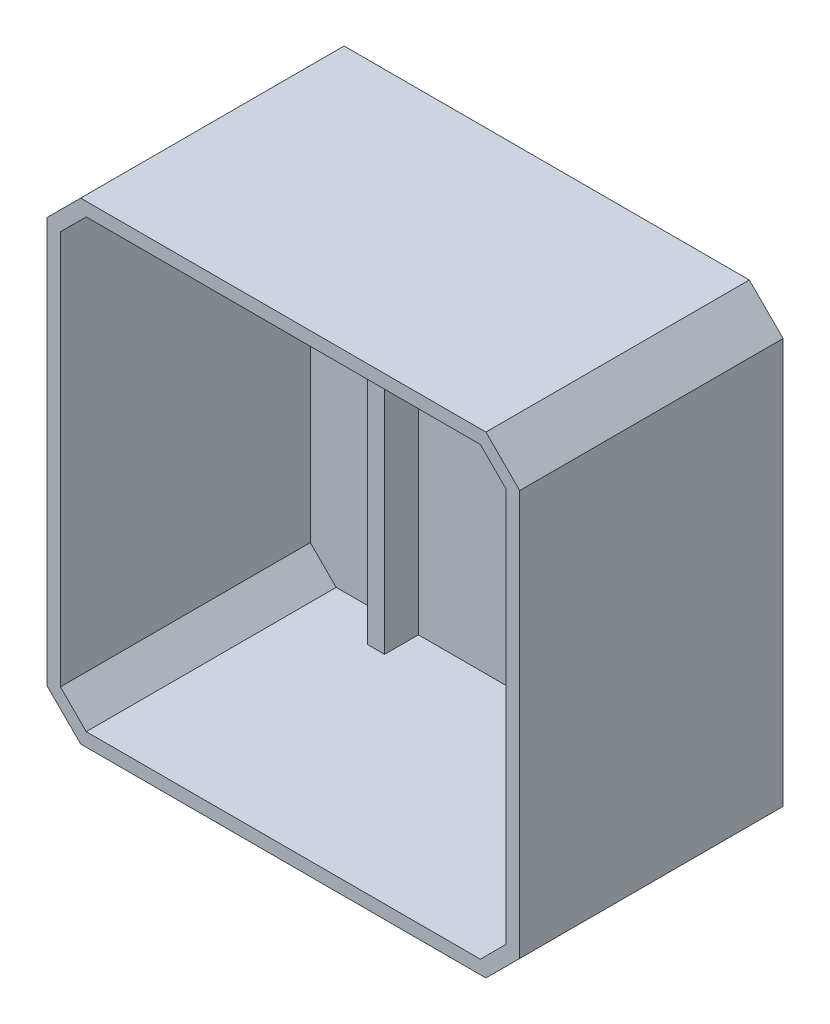
SolidWorks part; units mm, degrees
ref_plane "Front Plane" through (0, 0, 0) normal (0, 0, 1) x (1, 0, 0)
ref_plane "Top Plane" through (0, 0, 0) normal (0, 1, 0) x (1, 0, 0)
ref_plane "Right Plane" through (0, 0, 0) normal (1, 0, 0) x (0, 0, -1)
other "Graphic1"
other "Graphic (Closed) -1"
sketch "Sketch1" plane through (0, 0, 0) normal (0, 0, 1) x (1, 0, 0)
  line L1 (51.8222, 34.9266) -> (121.8222, 34.9266)
  line L2 (51.8222, 34.9266) -> (51.8222, -35.0734)
  line L3 (51.8222, -35.0734) -> (121.8222, -35.0734)
  line L4 (121.8222, 34.9266) -> (121.8222, -35.0734)
  dimension "D1" = 70
  dimension "D2" = 70
ref_plane "Plane1" through (0, 0, -39) normal (0, 0, 1) x (1, 0, 0)
extrude "Boss-Extrude1" add sketch "Sketch1" against normal blind 39
chamfer "Chamfer1" distance 5 angle 45 4 edges at (121.8222, -35.0734, -19.5) (51.8222, -35.0734, -19.5) (51.8222, 34.9266, -19.5) (121.8222, 34.9266, -19.5)
shell "Shell1" thickness 2
sketch "Sketch3" plane through (0, 0, -37) normal (0, 0, 1) x (1, 0, 0)
  line L0 (115.9938, 32.9266) -> (57.6506, 32.9266) construction
  line L1 (67.3222, 32.9266) -> (69.8222, 32.9266)
  line L2 (67.3222, 32.9266) -> (67.3222, -33.0734)
  line L3 (67.3222, -33.0734) -> (69.8222, -33.0734)
  line L4 (69.8222, 32.9266) -> (69.8222, -33.0734)
  line L5 (57.6506, -33.0734) -> (115.9938, -33.0734) construction
  line L6 (53.8222, 29.0982) -> (53.8222, -29.2449) construction
  line L8 (86.8222, 32.9266) -> (86.8222, -50.5449) construction
  line L9 (106.3222, -33.0734) -> (103.8222, -33.0734)
  line L10 (103.8222, 32.9266) -> (103.8222, -33.0734)
  line L11 (106.3222, 32.9266) -> (103.8222, 32.9266)
  line L12 (106.3222, 32.9266) -> (106.3222, -33.0734)
  dimension "D1" = 2.5
  dimension "D2" = 13.5
extrude "Boss-Extrude2" add sketch "Sketch3" along normal blind 5
